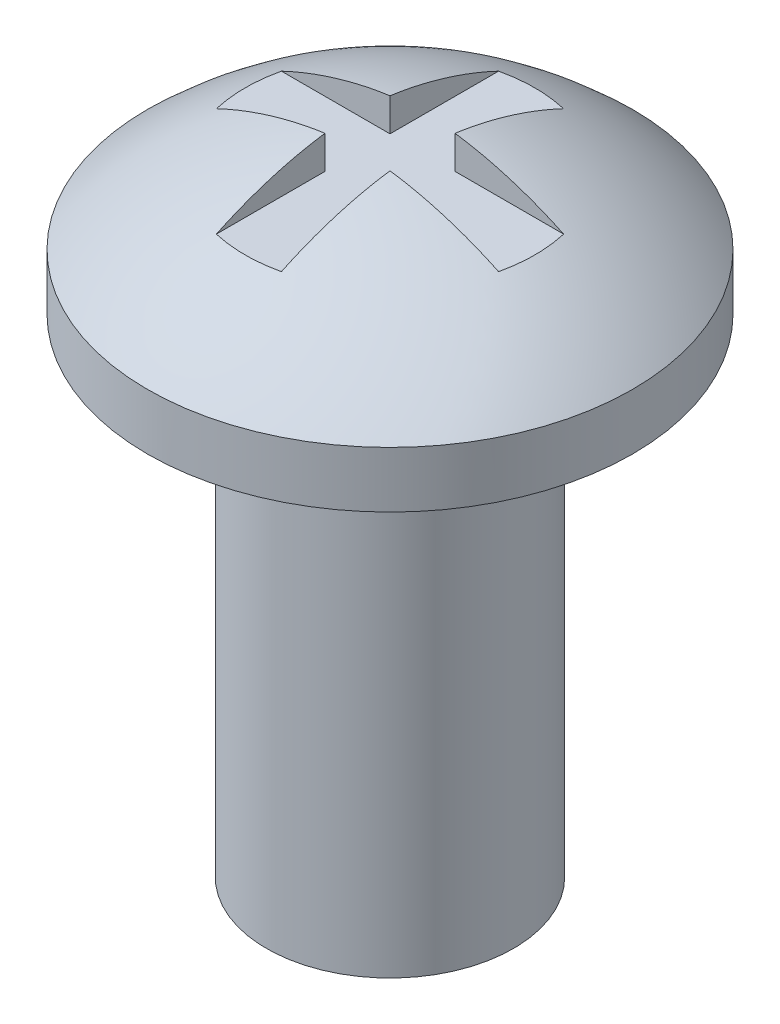
SolidWorks part; units mm, degrees
ref_plane "Front Plane" through (0, 0, 0) normal (0, 0, 1) x (1, 0, 0)
ref_plane "Top Plane" through (0, 0, 0) normal (0, 1, 0) x (1, 0, 0)
ref_plane "Right Plane" through (0, 0, 0) normal (1, 0, 0) x (0, 0, -1)
sketch "Sketch1" plane through (0, 0, 0) normal (0, 0, 1) x (1, 0, 0)
  line L0 (0, 0) -> (0, 12.7) construction
  line L1 (0, 0) -> (2.413, 0)
  line L2 (2.413, 0) -> (2.413, 9.525)
  line L3 (2.413, 9.525) -> (4.7371, 9.525)
  line L5 (4.7371, 10.6187) -> (4.7371, 9.525)
  line L6 (0, 0) -> (0, 12.7)
  arc A0 (0, 12.7) -> (4.7371, 10.6187) centre (-0.5579, 4.9986) cw
  dimension "D5" = 7.7216
  dimension "D1" = 12.7
  dimension "D2" = 4.826
  dimension "D3" = 9.4742
  dimension "D4" = 9.525
revolve "Revolve1" add sketch "Sketch1" angle 360 about L6
sketch "Sketch2" plane through (0, 0, 0) normal (0, 0, 1) x (1, 0, 0)
  line L0 (0, 11.938) -> (2.8285, 11.938)
  line L1 (0, 12.7) -> (0, 11.938)
  arc A0 (4.7371, 10.6187) -> (0, 12.7) centre (-0.5579, 4.9986) ccw construction
  arc A1 (2.8285, 11.938) -> (0, 12.7) centre (-0.5579, 4.9986) ccw
  dimension "D1" = 0.762
extrude "Cut-Extrude1" cut sketch "Sketch2" against normal mid plane 1.27
pattern_circular "CirPattern1" count 4 over 360 about axis through (0, 0, 0) along (0, 1, 0) of "Cut-Extrude1"
fillet "Fillet1" [suppressed] radius 0.254
chamfer "Chamfer1" [suppressed] distance 1.27 angle 45
